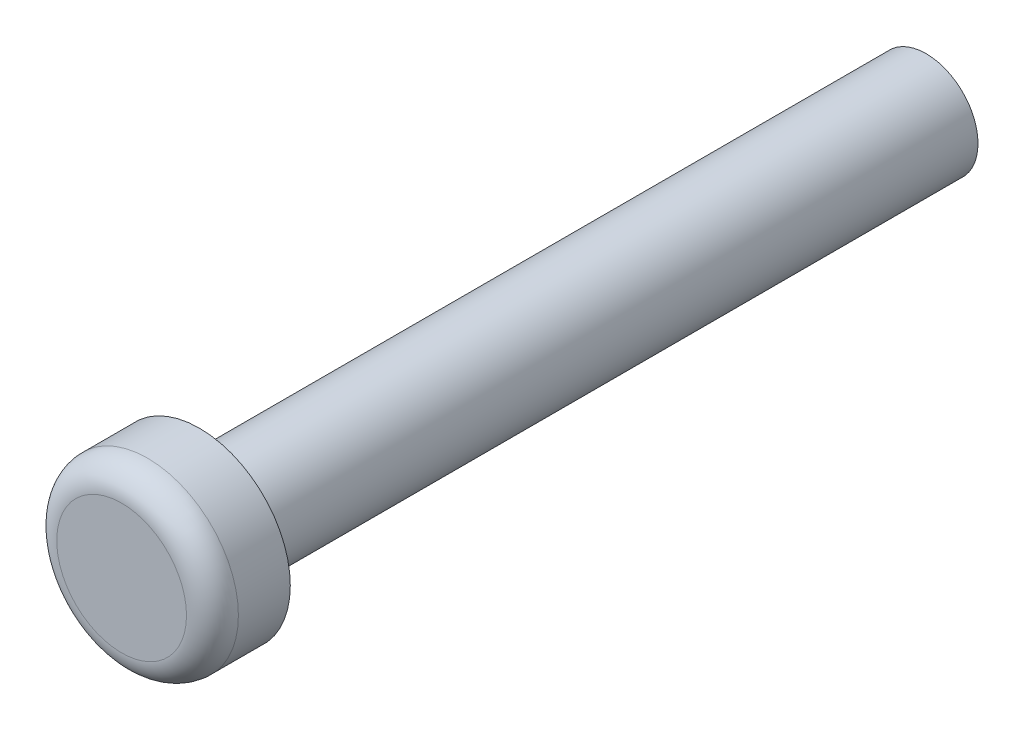
SolidWorks part; units mm, degrees
material "Plain Carbon Steel"
ref_plane "Front Plane" through (0, 0, 0) normal (0, 0, 1) x (1, 0, 0)
ref_plane "Top Plane" through (0, 0, 0) normal (0, 1, 0) x (1, 0, 0)
ref_plane "Right Plane" through (0, 0, 0) normal (1, 0, 0) x (0, 0, -1)
sketch "Sketch1" plane through (0, 0, 0) normal (0, 0, 1) x (1, 0, 0)
  circle A1 centre (0, 0) radius 4.445
  dimension "D2" = 8.89
extrude "Boss-Extrude1" add sketch "Sketch1" along normal blind 3.81
fillet "Fillet2" radius 1.27 1 edges at (4.445, 0, 3.81)
sketch "Sketch2" plane through (0, 0, 0) normal (0, 0, -1) x (-1, 0, 0)
  circle A0 centre (0, 0) radius 2.54
  dimension "D1" = 5.08
extrude "Boss-Extrude2" add sketch "Sketch2" along normal blind 35.56
